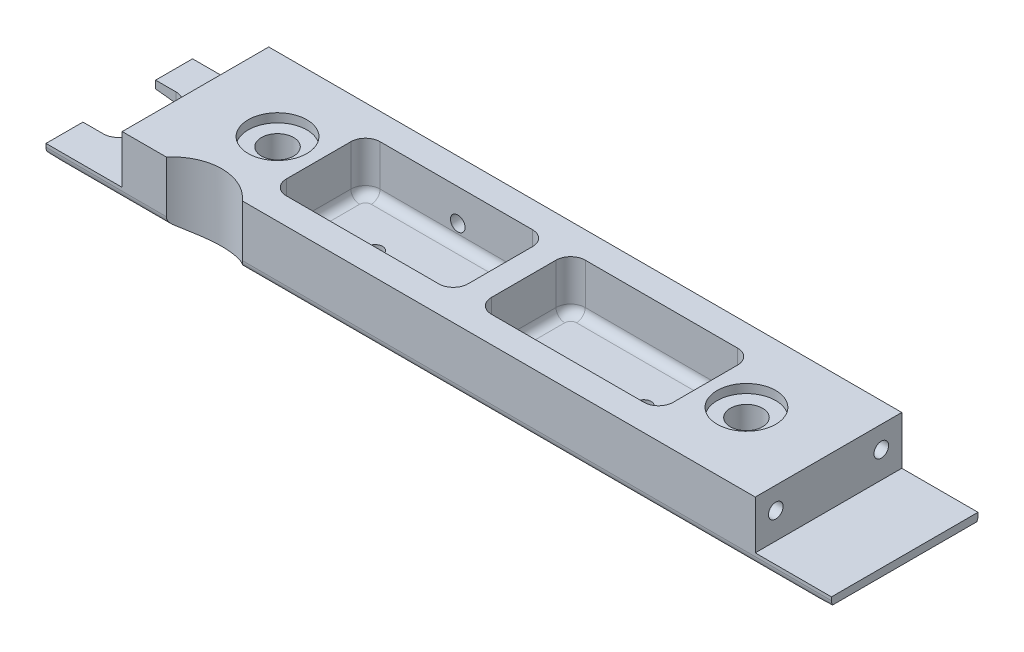
SolidWorks part; units mm, degrees
ref_plane "前视基准面" through (0, 0, 0) normal (0, 0, 1) x (1, 0, 0)
ref_plane "上视基准面" through (0, 0, 0) normal (0, 1, 0) x (1, 0, 0)
ref_plane "右视基准面" through (0, 0, 0) normal (1, 0, 0) x (0, 0, -1)
sketch "草图1" plane through (0, 0, 0) normal (0, 0, 1) x (1, 0, 0)
  line L48 (992.2947, 1041.6391) -> (1208.2947, 1041.6391)
  line L50 (1038.8657, 1016.6391) -> (1161.7236, 1016.6391)
  line L53 (1100.2947, 997.4238) -> (1100.2947, 1058.9811) construction
  line L54 (966.2947, 1022.5264) -> (966.2947, 1025.1391)
  line L55 (1234.2947, 1022.5264) -> (1234.2947, 1025.1391)
  line L56 (966.2947, 1025.1391) -> (992.2947, 1025.1391)
  line L57 (1208.2947, 1025.1391) -> (1208.2947, 1041.6391)
  line L58 (992.2947, 1025.1391) -> (992.2947, 1041.6391)
  line L59 (1208.2947, 1025.1391) -> (1234.2947, 1025.1391)
  arc A20 (966.2947, 1022.5264) -> (1038.6135, 1016.6455) centre (1098.2947, 2198.1558) ccw
  arc A21 (1038.6135, 1016.6455) -> (1038.8657, 1016.6391) centre (1038.8657, 1021.6391) ccw
  arc A22 (1161.9759, 1016.6455) -> (1234.2947, 1022.5264) centre (1102.2947, 2198.1558) ccw
  arc A23 (1161.7236, 1016.6391) -> (1161.9759, 1016.6455) centre (1161.7236, 1021.6391) ccw
extrude "拉伸1" add sketch "草图1" along normal blind 50
sketch "草图2" plane through (1234.2947, 0, 0) normal (1, 0, 0) x (0, 0, -1)
  line L0 (-25, 1022.5264) -> (-25, 1042.8722) construction
  line L1 (-50, 1022.5264) -> (0, 1022.5264) construction
  line L2 (-25, 1042.8722) -> (-25, 1012.9558) construction
  line L3 (-38.192, 1016.6455) -> (-11.808, 1016.6455)
  line L4 (-50, 1016.6455) -> (0, 1016.6455) construction
  line L5 (-50, 1024.0112) -> (-50, 1025.1391)
  line L6 (-50, 1024.0112) -> (-50, 1041.6391)
  line L7 (-50, 1041.6391) -> (0, 1041.6391)
  line L8 (0, 1041.6391) -> (0, 1024.0112)
  arc A0 (-39.8295, 1016.9212) -> (-48.7637, 1021.5844) centre (-28.5924, 1049.3404) cw
  arc A1 (-38.192, 1016.6455) -> (-39.8295, 1016.9212) centre (-38.192, 1021.6455) cw
  arc A2 (-50, 1024.0112) -> (-48.7637, 1021.5844) centre (-47, 1024.0112) ccw
  arc A3 (0, 1024.0112) -> (-1.2363, 1021.5844) centre (-3, 1024.0112) cw
  arc A4 (-10.1705, 1016.9212) -> (-1.2363, 1021.5844) centre (-21.4076, 1049.3404) ccw
  arc A5 (-11.808, 1016.6455) -> (-10.1705, 1016.9212) centre (-11.808, 1021.6455) ccw
  point P14 (-39, 1016.6455)
  point P16 (-44, 1016.6455)
  dimension "D5" = 5
  dimension "D6" = 3
  dimension "D2" = 14
  dimension "D4" = 5
extrude "拉伸4" cut sketch "草图2" against normal through all flip side to cut contours A2 A0 A1 L3 A5 A4 A3 L8 L7 L6
sketch "草图3" plane through (0, 1041.6391, 0) normal (0, 1, 0) x (1, 0, 0)
  line L0 (1100.2947, 0) -> (1100.2947, -64.99) construction
  line L1 (1208.2947, 0) -> (992.2947, 0) construction
  line L2 (966.2947, -25) -> (1234.2947, -25) construction
  line L3 (1039.2947, -41) -> (1091.2947, -41)
  line L4 (1034.2947, -36) -> (1034.2947, -14)
  line L5 (1039.2947, -9) -> (1091.2947, -9)
  line L6 (1096.2947, -36) -> (1096.2947, -14)
  line L7 (966.2947, -50) -> (966.2947, 0) construction
  line L8 (1234.2947, -50) -> (1234.2947, 0) construction
  line L9 (1104.2947, -36) -> (1104.2947, -14)
  line L10 (1161.2947, -41) -> (1109.2947, -41)
  line L11 (1166.2947, -36) -> (1166.2947, -14)
  line L12 (1161.2947, -9) -> (1109.2947, -9)
  arc A0 (1034.2947, -14) -> (1039.2947, -9) centre (1039.2947, -14) cw
  arc A1 (1039.2947, -41) -> (1034.2947, -36) centre (1039.2947, -36) cw
  arc A2 (1096.2947, -36) -> (1091.2947, -41) centre (1091.2947, -36) cw
  arc A3 (1091.2947, -9) -> (1096.2947, -14) centre (1091.2947, -14) cw
  arc A4 (1109.2947, -9) -> (1104.2947, -14) centre (1109.2947, -14) ccw
  arc A5 (1104.2947, -36) -> (1109.2947, -41) centre (1109.2947, -36) ccw
  arc A6 (1161.2947, -41) -> (1166.2947, -36) centre (1161.2947, -36) ccw
  arc A7 (1166.2947, -14) -> (1161.2947, -9) centre (1161.2947, -14) ccw
  point P16 (1034.2947, -9)
  point P19 (1034.2947, -41)
  point P24 (1096.2947, -9)
  point P37 (1166.2947, -9)
  dimension "D5" = 5
  dimension "D6" = 5
  dimension "D1" = 62
  dimension "D2" = 32
  dimension "D3" = 16
  dimension "D4" = 4
extrude "拉伸5" cut sketch "草图3" against normal blind 17
fillet "圆角1" radius 3 16 edges at (1135.2947, 1024.6391, 9) (1164.8302, 1024.6391, 10.4645) (1166.2947, 1024.6391, 25) (1164.8302, 1024.6391, 39.5355) (1135.2947, 1024.6391, 41) (1105.7591, 1024.6391, 39.5355) (1104.2947, 1024.6391, 25) (1105.7591, 1024.6391, 10.4645) (1094.8302, 1024.6391, 10.4645) (1096.2947, 1024.6391, 25) (1094.8302, 1024.6391, 39.5355) (1065.2947, 1024.6391, 41) (1035.7591, 1024.6391, 39.5355) (1034.2947, 1024.6391, 25) (1035.7591, 1024.6391, 10.4645) (1065.2947, 1024.6391, 9)
sketch "草图4" plane through (0, 1041.6391, 0) normal (0, 1, 0) x (1, 0, 0)
  line L0 (1100.2947, 0) -> (1100.2947, -63.6002) construction
  line L1 (1208.2947, 0) -> (992.2947, 0) construction
  circle A0 centre (1020.2947, -25) radius 5.5
  circle A1 centre (1180.2947, -25) radius 5.5
  dimension "D1" = 11
  dimension "D2" = 11
  dimension "D3" = 160
  dimension "D5" = 25
  dimension "D4" = 80
extrude "拉伸6" cut sketch "草图4" against normal through all
sketch "草图5" plane through (0, 1041.6391, 0) normal (0, 1, 0) x (1, 0, 0)
  circle A0 centre (1020.2947, -25) radius 10
  circle A1 centre (1180.2947, -25) radius 10
  dimension "D1" = 20
  dimension "D2" = 20
extrude "拉伸7" cut sketch "草图5" against normal blind 3
sketch "草图6" plane through (0, 1016.6455, 0) normal (0, -1, 0) x (1, 0, 0)
  circle A0 centre (1180.2947, 25) radius 8.5
  circle A1 centre (1020.2947, 25) radius 8.5
  dimension "D1" = 17
  dimension "D2" = 17
extrude "拉伸8" cut sketch "草图6" against normal blind 14
sketch "草图7" plane through (992.2947, 0, 0) normal (-1, 0, 0) x (0, 0, 1)
  line L0 (25, 1041.6391) -> (25, 1025.1391) construction
  line L1 (50, 1041.6391) -> (0, 1041.6391) construction
  line L2 (50, 1025.1391) -> (0, 1025.1391) construction
  circle A0 centre (7, 1034.1391) radius 2.5
  circle A1 centre (43, 1034.1391) radius 2.5
  dimension "D1" = 5
  dimension "D2" = 5
  dimension "D3" = 36
  dimension "D4" = 18
  dimension "D5" = 7.5
extrude "拉伸9" cut sketch "草图7" against normal blind 21
ref_plane "基准面2" through (1100.2947, 0, 0) normal (-1, 0, 0) x (0, 0, 1)
mirror "镜向1" about plane through (1100.2947, 0, 0) normal (-1, 0, 0) of "拉伸9"
sketch "草图8" plane through (0, 1016.6455, 0) normal (0, -1, 0) x (1, 0, 0)
  line L2 (1100.2947, 9.075) -> (1100.2947, -9.075) construction
  circle A0 centre (1020.2947, 61) radius 17
  dimension "D2" = 34
  dimension "D3" = 80
extrude "拉伸10" cut sketch "草图8" against normal through all
hole_wizard "M6 螺纹孔1" positions "草图11" profile "草图10" tap size "M6" standard "ISO"
sketch "草图11" plane through (0, 0, 0) normal (0, 0, -1) x (-1, 0, 0)
  line L0 (-1208.2947, 1025.1391) -> (-1208.2947, 1041.6391) construction
  point P1 (-1065.7947, 1030.7435)
  point P3 (-1165.7947, 1030.7435)
  dimension "D1" = 100
  dimension "D2" = 42.5
sketch "草图10" plane through (1065.7947, 1030.7435, 0) normal (1, 0, 0) x (0, 1, 0)
  line L0 (0, 0) -> (0, 16.5022)
  line L1 (0, 16.5022) -> (2.5, 15)
  line L2 (2.5, 15) -> (2.5, 0)
  line L5 (2.5, 0) -> (0, 0)
  line L10 (0, 16.5022) -> (-2.5, 15) construction
  line L11 (0, -6.35) -> (0, 107.95) construction
  dimension "螺纹孔钻头直径" = 5
  dimension "螺纹孔钻头深度" = 15
  dimension "导头角度" = 118
cosmetic thread "孔螺蚊线1" parameters "D1"=12, "D2"=6
cosmetic thread "孔螺蚊线2" parameters "D1"=9, "D2"=6
hole_wizard "M6 螺纹孔2" positions "草图13" profile "草图12" tap size "M6" standard "ISO"
sketch "草图13" plane through (0, 1016.6455, 0) normal (0, -1, 0) x (1, 0, 0)
  line L0 (1038.6135, 38.192) -> (1038.6135, 11.808) construction
  line L2 (966.2947, 0) -> (1234.2947, 0) construction
  circle A0 centre (1180.2947, 25) radius 8.5 construction
  point P0 (1053.6135, 25)
  point P1 (1145.2947, 25)
  dimension "D1" = 15
  dimension "D2" = 35
  dimension "D3" = 25
sketch "草图12" plane through (1053.6135, 1016.6455, 25) normal (1, 0, 0) x (0, 0, -1)
  line L0 (0, 0) -> (0, 16.5022)
  line L1 (0, 16.5022) -> (2.5, 15)
  line L2 (2.5, 15) -> (2.5, 0)
  line L5 (2.5, 0) -> (0, 0)
  line L10 (0, 16.5022) -> (-2.5, 15) construction
  line L11 (0, -6.35) -> (0, 107.95) construction
  dimension "螺纹孔钻头直径" = 5
  dimension "螺纹孔钻头深度" = 15
  dimension "导头角度" = 118
cosmetic thread "孔螺蚊线3" parameters "D1"=7.9936, "D2"=6
cosmetic thread "孔螺蚊线4" parameters "D1"=7.9936, "D2"=6
sketch "草图14" plane through (0, 1025.1391, 0) normal (0, 1, 0) x (1, 0, 0)
  line L3 (978.2947, -17.1534) -> (978.2947, -32.8466)
  line L5 (966.2947, -12.6) -> (973.2947, -12.6)
  line L6 (966.2947, -37.4) -> (973.2947, -37.4)
  line L7 (966.2947, -49.6068) -> (966.2947, -0.3932) construction
  line L8 (966.2947, -37.4) -> (966.2947, -12.6)
  arc A1 (978.2947, -17.1534) -> (973.2947, -12.6) centre (973.2947, -17.6219) ccw
  arc A2 (973.2947, -37.4) -> (978.2947, -32.8466) centre (973.2947, -32.3781) ccw
extrude "切除-拉伸1" cut sketch "草图14" against normal blind 10
